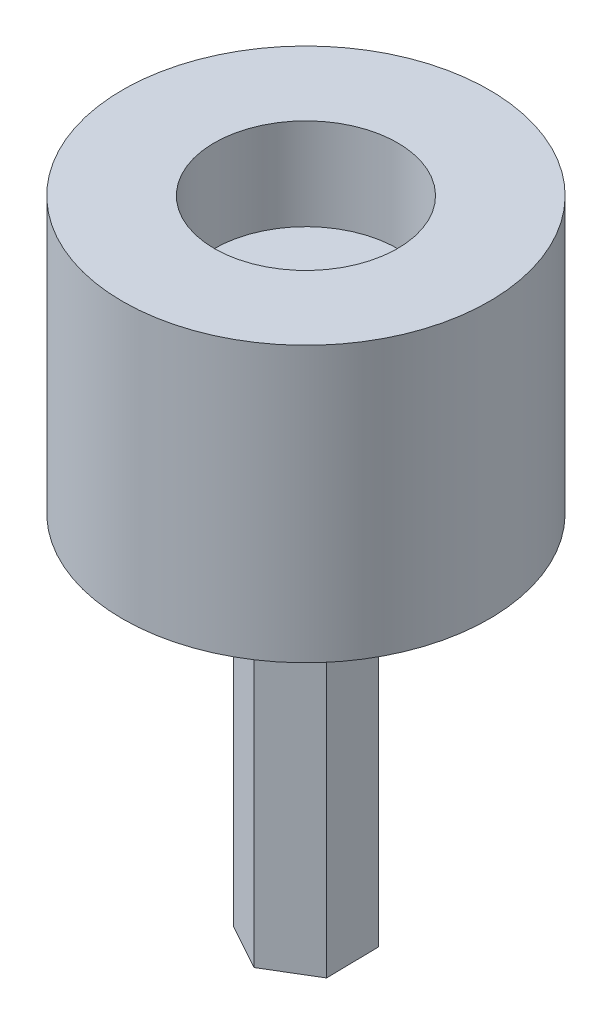
SolidWorks part; units mm, degrees
ref_plane "Front Plane" through (0, 0, 0) normal (0, 0, 1) x (1, 0, 0)
ref_plane "Top Plane" through (0, 0, 0) normal (0, 1, 0) x (1, 0, 0)
ref_plane "Right Plane" through (0, 0, 0) normal (1, 0, 0) x (0, 0, -1)
sketch "Sketch1" plane through (0, 0, 0) normal (0, 1, 0) x (1, 0, 0)
  circle A0 centre (-10.4911, 0.6473) radius 10
  dimension "D1" = 20
extrude "Boss-Extrude1" add sketch "Sketch1" along normal blind 15
sketch "Sketch2" plane through (0, 15, 0) normal (0, 1, 0) x (1, 0, 0)
  circle A0 centre (-10.4911, 0.6473) radius 5
  circle A1 centre (-10.4911, 0.6473) radius 10 construction
  dimension "D1" = 10
extrude "Cut-Extrude1" cut sketch "Sketch2" against normal blind 5
sketch "Sketch3" plane through (0, 0, 0) normal (0, -1, 0) x (-1, 0, 0)
  line L1 (8.0154, 2.1321) -> (7.9674, -0.7543)
  line L2 (7.9674, -0.7543) -> (10.443, -2.239)
  line L3 (10.443, -2.239) -> (12.9667, -0.8375)
  line L4 (12.9667, -0.8375) -> (13.0147, 2.0489)
  line L5 (13.0147, 2.0489) -> (10.5391, 3.5337)
  line L6 (10.5391, 3.5337) -> (8.0154, 2.1321)
  circle A0 centre (10.4911, 0.6473) radius 2.5 construction
  circle A1 centre (10.4911, 0.6473) radius 10 construction
  point P10 (0, 0)
  dimension "D1" = 5
extrude "Boss-Extrude2" add sketch "Sketch3" along normal blind 20
fillet "Fillet2" radius 2 6 edges at (-9.2773, 0, -2.8329) (-7.9914, 0, -0.6889) (-9.2052, 0, 1.4966) (-11.7049, 0, 1.5382) (-12.9907, 0, -0.6057) (-11.7769, 0, -2.7913)
